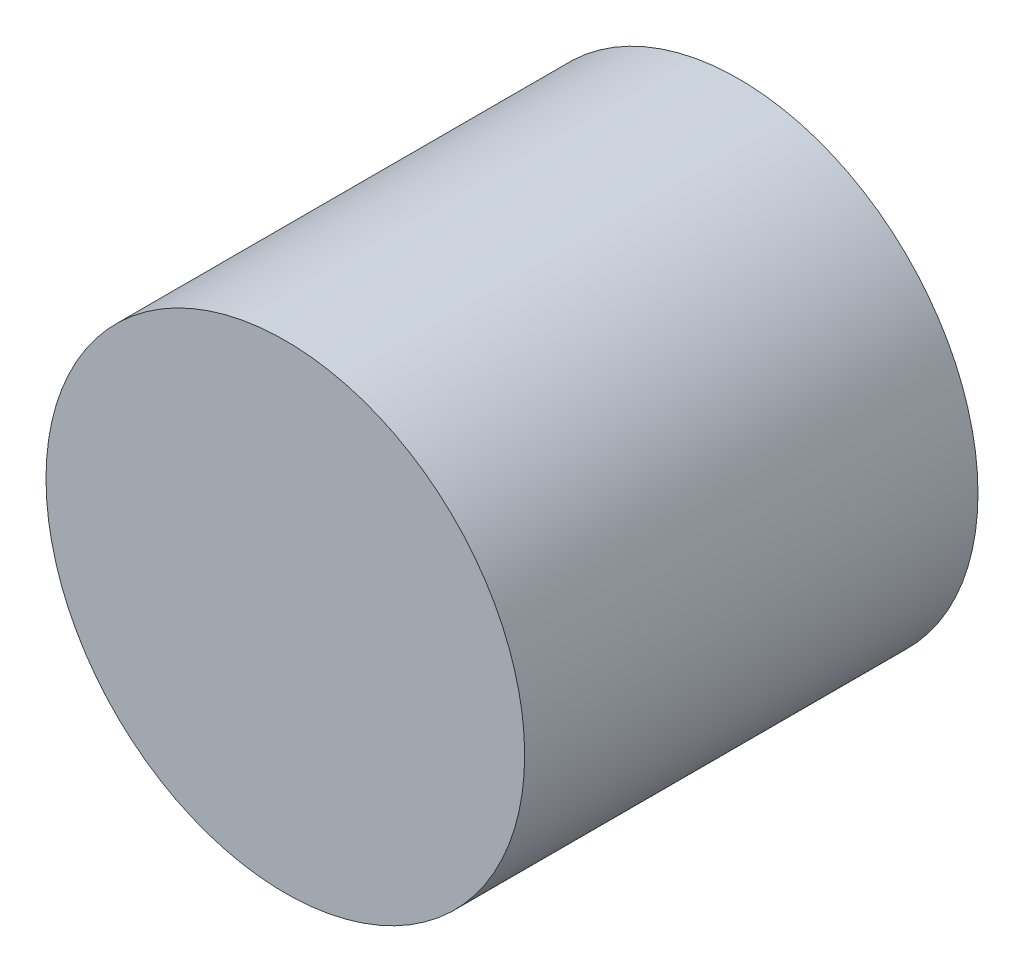
SolidWorks part; units mm, degrees
material "Nickel"
ref_plane "Front Plane" through (0, 0, 0) normal (0, 0, 1) x (1, 0, 0)
ref_plane "Top Plane" through (0, 0, 0) normal (0, 1, 0) x (1, 0, 0)
ref_plane "Right Plane" through (0, 0, 0) normal (1, 0, 0) x (0, 0, -1)
sketch "Sketch1" plane through (0, 0, 0) normal (0, 0, 1) x (1, 0, 0)
  circle A0 centre (0, 0) radius 47.512
extrude "Boss-Extrude1" add sketch "Sketch1" along normal blind 90
